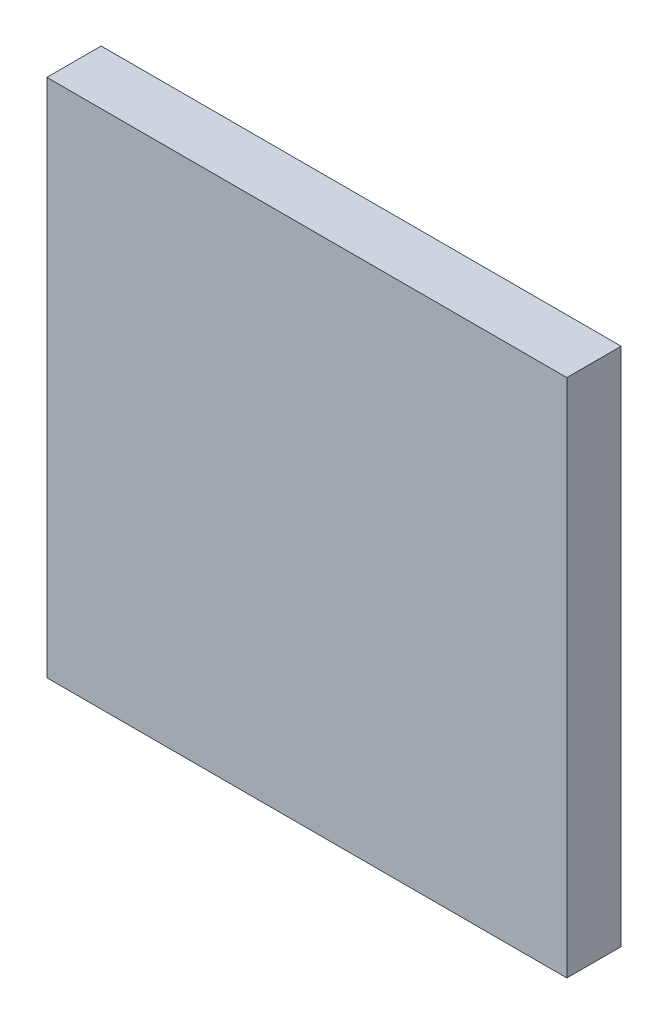
SolidWorks part; units mm, degrees
ref_plane "Front Plane" through (0, 0, 0) normal (0, 0, 1) x (1, 0, 0)
ref_plane "Top Plane" through (0, 0, 0) normal (0, 1, 0) x (1, 0, 0)
ref_plane "Right Plane" through (0, 0, 0) normal (1, 0, 0) x (0, 0, -1)
sketch "Sketch1" plane through (0, 0, 0) normal (0, 0, 1) x (1, 0, 0)
  line L1 (-4.5, 4.5) -> (4.5, 4.5)
  line L2 (-4.5, 4.5) -> (-4.5, -4.5)
  line L3 (-4.5, -4.5) -> (4.5, -4.5)
  line L4 (4.5, 4.5) -> (4.5, -4.5)
  dimension "D1" = 9
  dimension "D2" = 9
  dimension "D3" = 4.5
  dimension "D4" = 4.5
extrude "Boss-Extrude1" add sketch "Sketch1" along normal blind 0.9398
